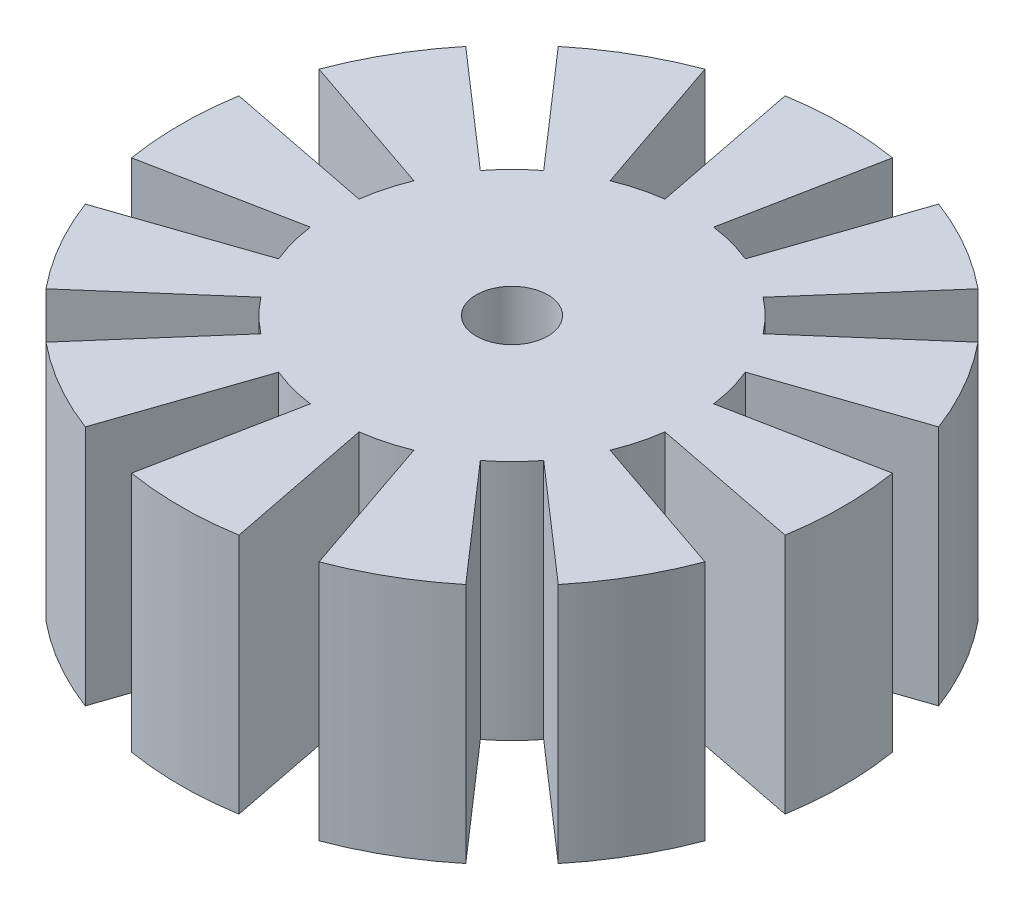
SolidWorks part; units mm, degrees
material "Ceramic Porcelain"
ref_plane "Front Plane" through (0, 0, 0) normal (0, 0, 1) x (1, 0, 0)
ref_plane "Top Plane" through (0, 0, 0) normal (0, 1, 0) x (1, 0, 0)
ref_plane "Right Plane" through (0, 0, 0) normal (1, 0, 0) x (0, 0, -1)
sketch "Sketch1" plane through (0, 0, 0) normal (0, 1, 0) x (1, 0, 0)
  line L0 (-16.3142, -6.6862) -> (-8.2639, -3.934)
  line L1 (-6.9056, -6.2867) -> (-13.3142, -11.8824)
  line L2 (-10.7304, -14.4661) -> (-5.1348, -8.0575)
  line L3 (-2.7821, -9.4159) -> (-5.5343, -17.4661)
  line L4 (-2.0048, -18.4118) -> (-0.3631, -10.064)
  line L5 (2.3536, -10.064) -> (3.9952, -18.4118)
  line L6 (7.5247, -17.4661) -> (4.7725, -9.4159)
  line L7 (7.1253, -8.0575) -> (12.7209, -14.4661)
  line L8 (15.3046, -11.8824) -> (8.896, -6.2867)
  line L9 (10.2544, -3.934) -> (18.3046, -6.6862)
  line L10 (19.2504, -3.1567) -> (10.9025, -1.5151)
  line L11 (10.9025, 1.2016) -> (19.2504, 2.8433)
  line L12 (18.3046, 6.3728) -> (10.2544, 3.6206)
  line L13 (8.896, 5.9733) -> (15.3046, 11.5689)
  line L14 (12.7209, 14.1527) -> (7.1253, 7.7441)
  line L15 (4.7725, 9.1025) -> (7.5247, 17.1527)
  line L16 (3.9952, 18.0984) -> (2.3536, 9.7506)
  line L17 (-0.3631, 9.7506) -> (-2.0048, 18.0984)
  line L18 (-5.5343, 17.1527) -> (-2.7821, 9.1025)
  line L19 (-5.1348, 7.7441) -> (-10.7304, 14.1527)
  line L20 (-13.3142, 11.5689) -> (-6.9056, 5.9733)
  line L21 (-8.2639, 3.6206) -> (-16.3142, 6.3728)
  line L22 (-17.2599, 2.8433) -> (-8.9121, 1.2016)
  line L24 (-8.9121, -1.5151) -> (-17.2599, -3.1567)
  arc A0 (-5.5343, 17.1527) -> (-10.7304, 14.1527) centre (0.9952, -0.1567) ccw
  circle A1 centre (0.9952, -0.1567) radius 2
  arc A2 (10.2544, -3.934) -> (10.9025, -1.5151) centre (0.9952, -0.1567) ccw
  arc A3 (10.9025, 1.2016) -> (10.2544, 3.6206) centre (0.9952, -0.1567) ccw
  arc A4 (3.9952, 18.0984) -> (-2.0048, 18.0984) centre (0.9952, -0.1567) ccw
  arc A5 (12.7209, 14.1527) -> (7.5247, 17.1527) centre (0.9952, -0.1567) ccw
  arc A6 (18.3046, 6.3728) -> (15.3046, 11.5689) centre (0.9952, -0.1567) ccw
  arc A7 (19.2504, -3.1567) -> (19.2504, 2.8433) centre (0.9952, -0.1567) ccw
  arc A8 (15.3046, -11.8824) -> (18.3046, -6.6862) centre (0.9952, -0.1567) ccw
  arc A9 (7.5247, -17.4661) -> (12.7209, -14.4661) centre (0.9952, -0.1567) ccw
  arc A10 (-2.0048, -18.4118) -> (3.9952, -18.4118) centre (0.9952, -0.1567) ccw
  arc A11 (-10.7304, -14.4661) -> (-5.5343, -17.4661) centre (0.9952, -0.1567) ccw
  arc A12 (-16.3142, -6.6862) -> (-13.3142, -11.8824) centre (0.9952, -0.1567) ccw
  arc A13 (-17.2599, 2.8433) -> (-17.2599, -3.1567) centre (0.9952, -0.1567) ccw
  arc A14 (8.896, 5.9733) -> (7.1253, 7.7441) centre (0.9952, -0.1567) ccw
  arc A15 (4.7725, 9.1025) -> (2.3536, 9.7506) centre (0.9952, -0.1567) ccw
  arc A16 (-0.3631, 9.7506) -> (-2.7821, 9.1025) centre (0.9952, -0.1567) ccw
  arc A17 (-5.1348, 7.7441) -> (-6.9056, 5.9733) centre (0.9952, -0.1567) ccw
  arc A18 (-8.2639, 3.6206) -> (-8.9121, 1.2016) centre (0.9952, -0.1567) ccw
  arc A19 (-13.3142, 11.5689) -> (-16.3142, 6.3728) centre (0.9952, -0.1567) ccw
  arc A20 (-8.9121, -1.5151) -> (-8.2639, -3.934) centre (0.9952, -0.1567) ccw
  arc A21 (-6.9056, -6.2867) -> (-5.1348, -8.0575) centre (0.9952, -0.1567) ccw
  arc A22 (-2.7821, -9.4159) -> (-0.3631, -10.064) centre (0.9952, -0.1567) ccw
  arc A23 (2.3536, -10.064) -> (4.7725, -9.4159) centre (0.9952, -0.1567) ccw
  arc A24 (7.1253, -8.0575) -> (8.896, -6.2867) centre (0.9952, -0.1567) ccw
  point P2 (12.2301, 19.3027)
  point P4 (20.6396, 11.185)
  point P5 (-11.1136, -21.1297)
  point P6 (24.175, -0.1567)
  point P7 (22.5283, -12.5888)
  point P8 (13.6273, -22.0361)
  point P9 (0.9952, -26.282)
  point P10 (-23.2821, 13.8598)
  point P11 (-21.6414, -13.226)
  point P12 (-24.175, -0.1567)
  point P13 (-14.2692, 26.282)
  point P14 (0.9952, 23.9275)
  point P15 (3.9952, -0.1567)
  point P16 (3.9952, 23.9275)
  point P17 (3.5933, 1.3433)
  point P18 (-11.6711, 27.782)
  point P19 (2.4952, 2.4414)
  point P20 (-21.7821, 16.4579)
  point P21 (0.9952, 2.8433)
  point P22 (-24.175, 2.8433)
  point P23 (-0.5048, 2.4414)
  point P24 (-23.1414, -10.6279)
  point P25 (-1.6029, 1.3433)
  point P26 (-13.7116, -19.6297)
  point P27 (-2.0048, -0.1567)
  point P28 (-2.0048, -26.282)
  point P29 (-1.6029, -1.6567)
  point P30 (11.0292, -23.5361)
  point P31 (-0.5048, -2.7548)
  point P32 (21.0283, -15.1869)
  point P33 (0.9952, -3.1567)
  point P34 (24.175, -3.1567)
  point P35 (2.4952, -2.7548)
  point P36 (22.1396, 8.5869)
  point P37 (3.5933, -1.6567)
  point P38 (14.8282, 17.8027)
  point P40 (-2.0048, 23.9275)
  point P42 (-16.8673, 24.782)
  point P44 (-24.7821, 11.2617)
  point P46 (-24.175, -3.1567)
  point P48 (-20.1414, -15.8241)
  point P50 (-8.5155, -22.6297)
  point P52 (3.9952, -26.282)
  point P54 (16.2254, -20.5361)
  point P56 (24.0283, -9.9907)
  point P58 (24.175, 2.8433)
  point P60 (19.1396, 13.783)
  point P62 (9.632, 20.8027)
extrude "Boss-Extrude1" add sketch "Sketch1" along normal blind 13.5
